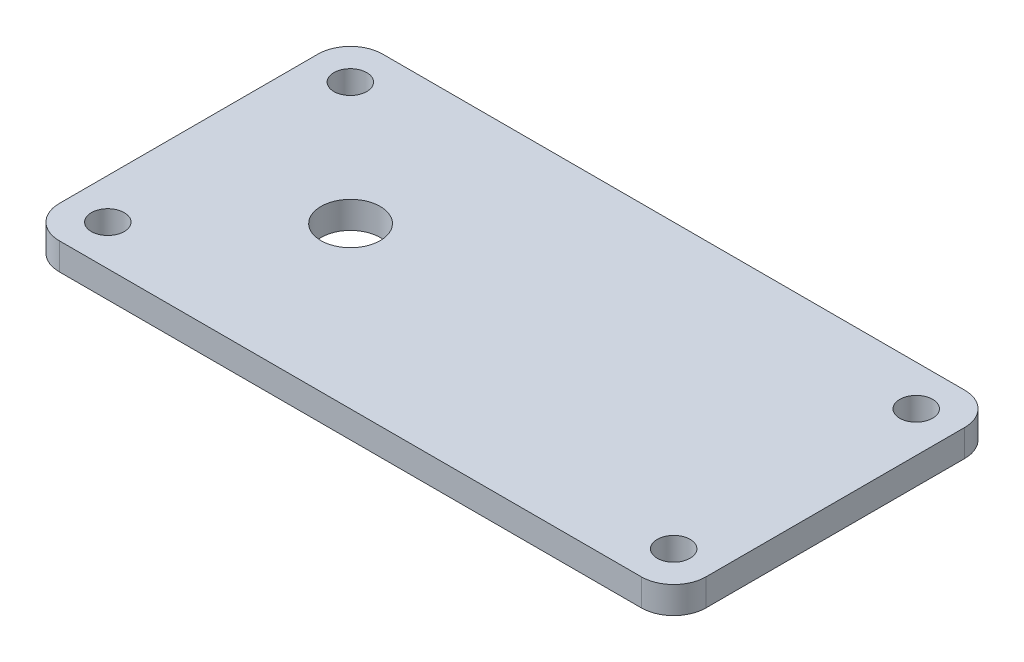
SolidWorks part; units mm, degrees
ref_plane "Front Plane" through (0, 0, 0) normal (0, 0, 1) x (1, 0, 0)
ref_plane "Top Plane" through (0, 0, 0) normal (0, 1, 0) x (1, 0, 0)
ref_plane "Right Plane" through (0, 0, 0) normal (1, 0, 0) x (0, 0, -1)
sketch "Sketch1" plane through (0, 0, 0) normal (0, 1, 0) x (1, 0, 0)
  line L1 (-60, 30) -> (60, 30)
  line L2 (-60, 30) -> (-60, -30)
  line L3 (-60, -30) -> (60, -30)
  line L4 (60, 30) -> (60, -30)
  line L5 (-60, 30) -> (60, -30) construction
  line L6 (-60, -30) -> (60, 30) construction
  point P0 (0, 0)
  dimension "D1" = 120
  dimension "D2" = 60
extrude "Boss-Extrude1" add sketch "Sketch1" along normal blind 5
sketch "Sketch2" plane through (0, 5, 0) normal (0, 1, 0) x (1, 0, 0)
  line L0 (-60, 30) -> (-60, -30) construction
  line L1 (60, 30) -> (-60, 30) construction
  circle A0 centre (-52.5, 22.5) radius 3.05
  dimension "D3" = 6.1
  dimension "D1" = 7.5
  dimension "D2" = 7.5
extrude "Cut-Extrude1" cut sketch "Sketch2" against normal through all
mirror "Mirror1" about plane through (0, 0, 0) normal (0, 0, 1) of "Cut-Extrude1"
mirror "Mirror2" about plane through (0, 0, 0) normal (1, 0, 0) of "Mirror1", "Cut-Extrude1"
sketch "Sketch3" plane through (0, 5, 0) normal (0, 1, 0) x (1, 0, 0)
  line L0 (-60, 0) -> (0.5004, -0.4065) construction
  line L1 (-60, 30) -> (-60, -30) construction
  circle A1 centre (-29.7498, -0.2033) radius 5.5
  dimension "D1" = 11
extrude "Cut-Extrude2" cut sketch "Sketch3" against normal through all
fillet "Fillet1" radius 6 4 edges at (-60, 2.5, -30) (60, 2.5, -30) (60, 2.5, 30) (-60, 2.5, 30)
equation "\"D2@Sketch2\"=\"D1@Sketch2\""
